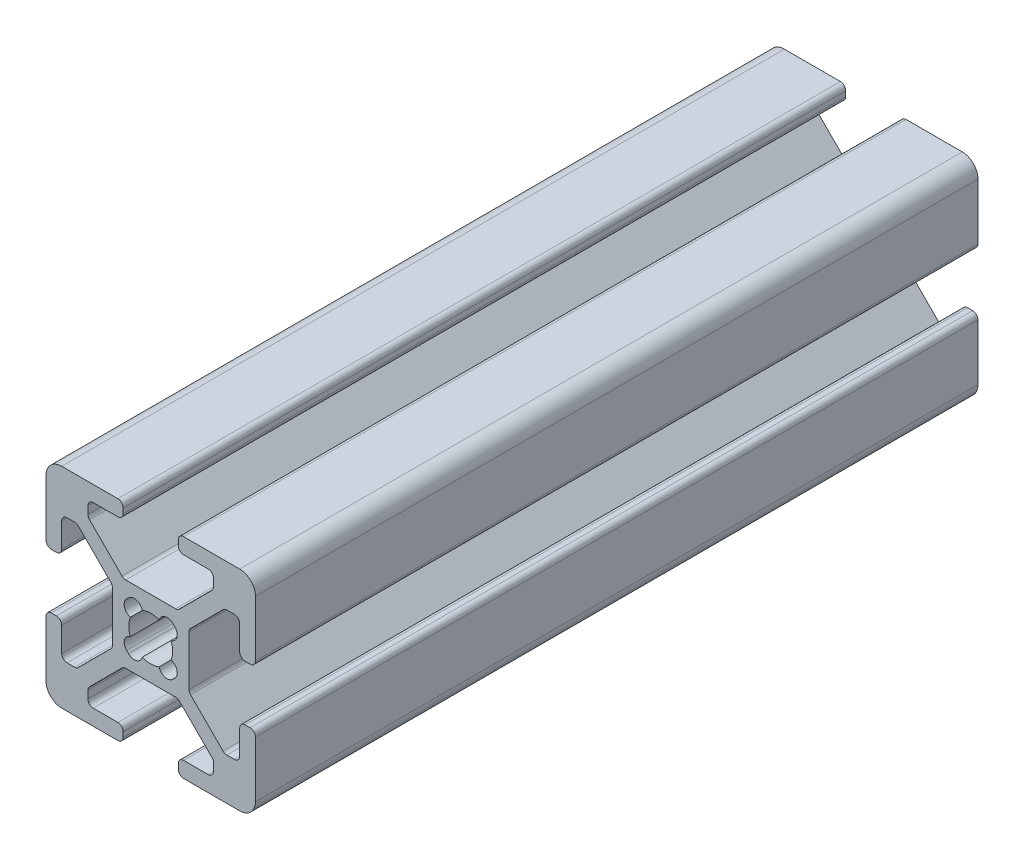
SolidWorks part; units mm, degrees
material "1060 Alloy"
ref_plane "Front Plane" through (0, 0, 0) normal (0, 0, 1) x (1, 0, 0)
ref_plane "Top Plane" through (0, 0, 0) normal (0, 1, 0) x (1, 0, 0)
ref_plane "Right Plane" through (0, 0, 0) normal (1, 0, 0) x (0, 0, -1)
sketch "Sketch2" plane through (0, 0, 0) normal (0, 0, 1) x (1, 0, 0)
  line L0 (-10, -3.138) -> (-10, -8.5)
  line L1 (-8.5, -10) -> (-3.138, -10)
  line L2 (-2.63, -9.492) -> (-2.63, -9.008)
  line L3 (-3.138, -8.5) -> (-5.487, -8.5)
  line L4 (-5.995, -7.992) -> (-5.995, -7.2662)
  line L5 (-5.8462, -6.907) -> (-2.743, -3.8038)
  line L6 (-2.3838, -3.655) -> (2.3841, -3.655)
  line L7 (2.7433, -3.8038) -> (5.8462, -6.9067)
  line L8 (5.995, -7.2659) -> (5.995, -7.992)
  line L9 (5.487, -8.5) -> (3.138, -8.5)
  line L10 (2.63, -9.008) -> (2.63, -9.492)
  line L11 (3.138, -10) -> (8.5, -10)
  line L12 (10, -8.5) -> (10, -3.138)
  line L13 (9.492, -2.63) -> (9.008, -2.63)
  line L14 (8.5, -3.138) -> (8.5, -5.487)
  line L15 (7.992, -5.995) -> (7.2662, -5.995)
  line L16 (6.907, -5.8462) -> (3.8038, -2.743)
  line L17 (3.655, -2.3838) -> (3.655, 2.3841)
  line L18 (3.8038, 2.7433) -> (6.9067, 5.8462)
  line L19 (7.2659, 5.995) -> (7.992, 5.995)
  line L20 (8.5, 5.487) -> (8.5, 3.138)
  line L21 (9.008, 2.63) -> (9.492, 2.63)
  line L22 (10, 3.138) -> (10, 8.5)
  line L23 (8.5, 10) -> (3.138, 10)
  line L24 (2.63, 9.492) -> (2.63, 9.008)
  line L25 (3.138, 8.5) -> (5.487, 8.5)
  line L26 (5.995, 7.992) -> (5.995, 7.2662)
  line L27 (5.8462, 6.907) -> (2.743, 3.8038)
  line L28 (2.3838, 3.655) -> (-2.3841, 3.655)
  line L29 (-2.7433, 3.8038) -> (-5.8462, 6.9067)
  line L30 (-5.995, 7.2659) -> (-5.995, 7.992)
  line L31 (-5.487, 8.5) -> (-3.138, 8.5)
  line L32 (-2.63, 9.008) -> (-2.63, 9.492)
  line L33 (-3.138, 10) -> (-8.5, 10)
  line L34 (-10, 8.5) -> (-10, 3.138)
  line L35 (-9.492, 2.63) -> (-9.008, 2.63)
  line L36 (-8.5, 3.138) -> (-8.5, 5.487)
  line L37 (-7.992, 5.995) -> (-7.2662, 5.995)
  line L38 (-6.907, 5.8462) -> (-3.8038, 2.743)
  line L39 (-3.655, 2.3838) -> (-3.655, -2.3841)
  line L40 (-3.8038, -2.7433) -> (-6.9067, -5.8462)
  line L41 (-7.2659, -5.995) -> (-7.992, -5.995)
  line L42 (-8.5, -5.487) -> (-8.5, -3.138)
  line L43 (-9.008, -2.63) -> (-9.492, -2.63)
  line L44 (-2.1245, 2.3045) -> (-2.3045, 2.1245)
  line L45 (2.3045, 2.1245) -> (2.1245, 2.3045)
  line L46 (2.1245, -2.3045) -> (2.3045, -2.1245)
  line L47 (-2.3045, -2.1245) -> (-2.1245, -2.3045)
  arc A0 (-10, -8.5) -> (-8.5, -10) centre (-8.5, -8.5) ccw
  arc A1 (-3.138, -10) -> (-2.63, -9.492) centre (-3.138, -9.492) ccw
  arc A2 (-2.63, -9.008) -> (-3.138, -8.5) centre (-3.138, -9.008) ccw
  arc A3 (-5.995, -7.992) -> (-5.487, -8.5) centre (-5.487, -7.992) ccw
  arc A4 (-5.8462, -6.907) -> (-5.995, -7.2662) centre (-5.487, -7.2662) ccw
  arc A5 (-2.3838, -3.655) -> (-2.743, -3.8038) centre (-2.3838, -4.163) ccw
  arc A6 (2.7433, -3.8038) -> (2.3841, -3.655) centre (2.3841, -4.163) ccw
  arc A7 (5.995, -7.2659) -> (5.8462, -6.9067) centre (5.487, -7.2659) ccw
  arc A8 (5.487, -8.5) -> (5.995, -7.992) centre (5.487, -7.992) ccw
  arc A9 (3.138, -8.5) -> (2.63, -9.008) centre (3.138, -9.008) ccw
  arc A10 (2.63, -9.492) -> (3.138, -10) centre (3.138, -9.492) ccw
  arc A11 (8.5, -10) -> (10, -8.5) centre (8.5, -8.5) ccw
  arc A12 (10, -3.138) -> (9.492, -2.63) centre (9.492, -3.138) ccw
  arc A13 (9.008, -2.63) -> (8.5, -3.138) centre (9.008, -3.138) ccw
  arc A14 (7.992, -5.995) -> (8.5, -5.487) centre (7.992, -5.487) ccw
  arc A15 (6.907, -5.8462) -> (7.2662, -5.995) centre (7.2662, -5.487) ccw
  arc A16 (3.655, -2.3838) -> (3.8038, -2.743) centre (4.163, -2.3838) ccw
  arc A17 (3.8038, 2.7433) -> (3.655, 2.3841) centre (4.163, 2.3841) ccw
  arc A18 (7.2659, 5.995) -> (6.9067, 5.8462) centre (7.2659, 5.487) ccw
  arc A19 (8.5, 5.487) -> (7.992, 5.995) centre (7.992, 5.487) ccw
  arc A20 (8.5, 3.138) -> (9.008, 2.63) centre (9.008, 3.138) ccw
  arc A21 (9.492, 2.63) -> (10, 3.138) centre (9.492, 3.138) ccw
  arc A22 (10, 8.5) -> (8.5, 10) centre (8.5, 8.5) ccw
  arc A23 (3.138, 10) -> (2.63, 9.492) centre (3.138, 9.492) ccw
  arc A24 (2.63, 9.008) -> (3.138, 8.5) centre (3.138, 9.008) ccw
  arc A25 (5.995, 7.992) -> (5.487, 8.5) centre (5.487, 7.992) ccw
  arc A26 (5.8462, 6.907) -> (5.995, 7.2662) centre (5.487, 7.2662) ccw
  arc A27 (2.3838, 3.655) -> (2.743, 3.8038) centre (2.3838, 4.163) ccw
  arc A28 (-2.7433, 3.8038) -> (-2.3841, 3.655) centre (-2.3841, 4.163) ccw
  arc A29 (-5.995, 7.2659) -> (-5.8462, 6.9067) centre (-5.487, 7.2659) ccw
  arc A30 (-5.487, 8.5) -> (-5.995, 7.992) centre (-5.487, 7.992) ccw
  arc A31 (-3.138, 8.5) -> (-2.63, 9.008) centre (-3.138, 9.008) ccw
  arc A32 (-2.63, 9.492) -> (-3.138, 10) centre (-3.138, 9.492) ccw
  arc A33 (-8.5, 10) -> (-10, 8.5) centre (-8.5, 8.5) ccw
  arc A34 (-10, 3.138) -> (-9.492, 2.63) centre (-9.492, 3.138) ccw
  arc A35 (-9.008, 2.63) -> (-8.5, 3.138) centre (-9.008, 3.138) ccw
  arc A36 (-7.992, 5.995) -> (-8.5, 5.487) centre (-7.992, 5.487) ccw
  arc A37 (-6.907, 5.8462) -> (-7.2662, 5.995) centre (-7.2662, 5.487) ccw
  arc A38 (-3.655, 2.3838) -> (-3.8038, 2.743) centre (-4.163, 2.3838) ccw
  arc A39 (-3.8038, -2.7433) -> (-3.655, -2.3841) centre (-4.163, -2.3841) ccw
  arc A40 (-7.2659, -5.995) -> (-6.9067, -5.8462) centre (-7.2659, -5.487) ccw
  arc A41 (-8.5, -5.487) -> (-7.992, -5.995) centre (-7.992, -5.487) ccw
  arc A42 (-8.5, -3.138) -> (-9.008, -2.63) centre (-9.008, -3.138) ccw
  arc A43 (-9.492, -2.63) -> (-10, -3.138) centre (-9.492, -3.138) ccw
  arc A44 (-1.9358, 0.8037) -> (-1.9358, -0.8037) centre (0, 0) ccw
  arc A45 (-2.3045, 2.1245) -> (-1.9358, 0.8037) centre (-1.748, 1.568) ccw
  arc A46 (-0.8037, 1.9358) -> (-2.1245, 2.3045) centre (-1.568, 1.748) ccw
  arc A47 (0.8037, 1.9358) -> (-0.8037, 1.9358) centre (0, 0) ccw
  arc A48 (2.1245, 2.3045) -> (0.8037, 1.9358) centre (1.568, 1.748) ccw
  arc A49 (1.9358, 0.8037) -> (2.3045, 2.1245) centre (1.748, 1.568) ccw
  arc A50 (1.9358, -0.8037) -> (1.9358, 0.8037) centre (0, 0) ccw
  arc A51 (2.3045, -2.1245) -> (1.9358, -0.8037) centre (1.748, -1.568) ccw
  arc A52 (0.8037, -1.9358) -> (2.1245, -2.3045) centre (1.568, -1.748) ccw
  arc A53 (-0.8037, -1.9358) -> (0.8037, -1.9358) centre (0, 0) ccw
  arc A54 (-2.1245, -2.3045) -> (-0.8037, -1.9358) centre (-1.568, -1.748) ccw
  arc A55 (-1.9358, -0.8037) -> (-2.3045, -2.1245) centre (-1.748, -1.568) ccw
extrude "Boss-Extrude1" add sketch "Sketch2" against normal blind 69
